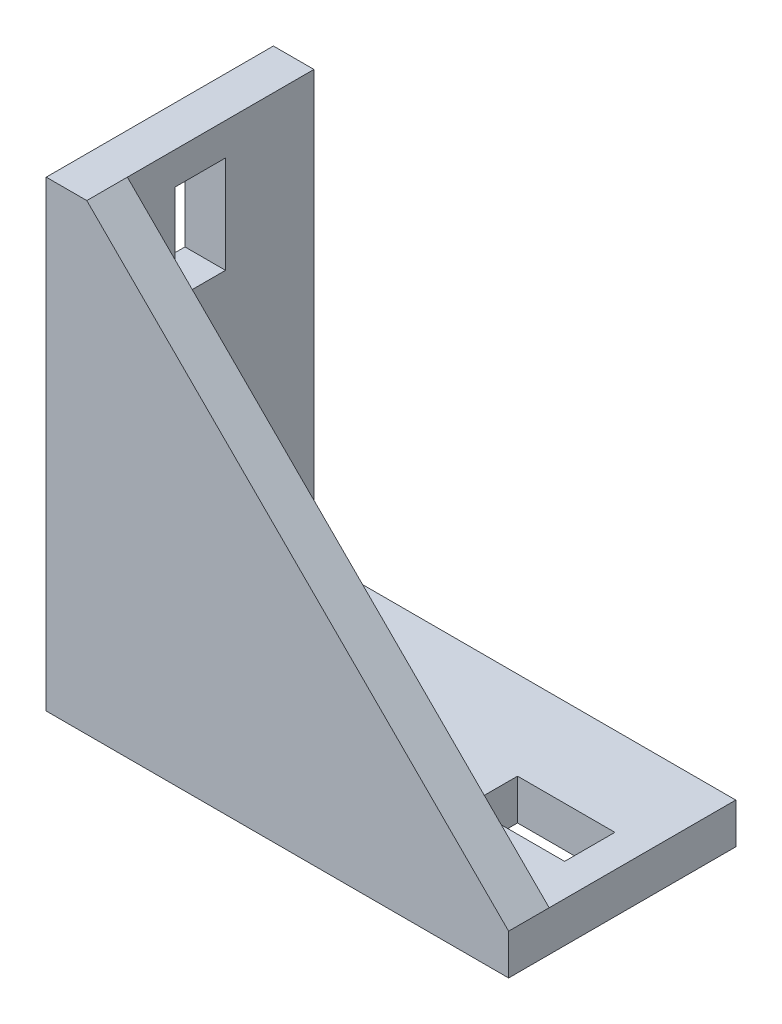
SolidWorks part; units mm, degrees
ref_plane "Front Plane" through (0, 0, 0) normal (0, 0, 1) x (1, 0, 0)
ref_plane "Top Plane" through (0, 0, 0) normal (0, 1, 0) x (1, 0, 0)
ref_plane "Right Plane" through (0, 0, 0) normal (1, 0, 0) x (0, 0, -1)
sketch "Sketch1" plane through (0, 0, 0) normal (0, 0, 1) x (1, 0, 0)
  line L0 (5, 57) -> (5, 5)
  line L1 (0, 0) -> (57, 0)
  line L2 (0, 0) -> (0, 57)
  line L3 (0, 57) -> (5, 57)
  line L4 (57, 5) -> (57, 0)
  line L5 (5, 5) -> (57, 5)
  dimension "D1" = 57
  dimension "D2" = 57
  dimension "D3" = 5
  dimension "D4" = 5
extrude "Boss-Extrude1" add sketch "Sketch1" along normal blind 28
sketch "Sketch2" plane through (0, 0, 28) normal (0, 0, 1) x (1, 0, 0)
  line L0 (5, 57) -> (57, 5)
  line L1 (5, 57) -> (5, 5)
  line L2 (5, 5) -> (57, 5)
extrude "Boss-Extrude2" add sketch "Sketch2" against normal blind 5
sketch "Sketch3" plane through (5, 0, 0) normal (1, 0, 0) x (0, 0, -1)
  line L0 (-28, 57) -> (0, 57) construction
  line L1 (-28, 57) -> (-23, 57) construction
  line L2 (-14, 57) -> (-14, 5) construction
  line L3 (-23, 5) -> (0, 5) construction
  line L7 (-17.1, 41) -> (-10.9, 41)
  line L8 (-17.1, 41) -> (-17.1, 53)
  line L9 (-17.1, 53) -> (-10.9, 53)
  line L10 (-10.9, 41) -> (-10.9, 53)
  line L11 (-17.1, 41) -> (-10.9, 53) construction
  line L12 (-17.1, 53) -> (-10.9, 41) construction
  line L13 (-17.1, 9) -> (-10.9, 9)
  line L14 (-17.1, 9) -> (-17.1, 21)
  line L15 (-17.1, 21) -> (-10.9, 21)
  line L16 (-10.9, 9) -> (-10.9, 21)
  line L17 (-17.1, 9) -> (-10.9, 21) construction
  line L18 (-17.1, 21) -> (-10.9, 9) construction
  point P9 (-14, 47)
  point P14 (-14, 15)
  point P21 (0, 0)
  dimension "D1" = 6.2
  dimension "D2" = 6.2
  dimension "D3" = 12
  dimension "D4" = 10
  dimension "D5" = 12
  dimension "D6" = 10
extrude "Cut-Extrude1" cut sketch "Sketch3" against normal blind 5
sketch "Sketch4" plane through (0, 5, 0) normal (0, 1, 0) x (1, 0, 0)
  line L0 (57, -28) -> (57, 0) construction
  line L1 (57, -14) -> (5, -14) construction
  line L2 (5, -23) -> (5, 0) construction
  line L4 (53, -17.1) -> (41, -17.1)
  line L5 (53, -17.1) -> (53, -10.9)
  line L6 (53, -10.9) -> (41, -10.9)
  line L7 (41, -17.1) -> (41, -10.9)
  line L8 (53, -17.1) -> (41, -10.9) construction
  line L9 (53, -10.9) -> (41, -17.1) construction
  line L10 (21, -17.1) -> (9, -17.1)
  line L11 (21, -17.1) -> (21, -10.9)
  line L12 (21, -10.9) -> (9, -10.9)
  line L13 (9, -17.1) -> (9, -10.9)
  line L14 (21, -17.1) -> (9, -10.9) construction
  line L15 (21, -10.9) -> (9, -17.1) construction
  point P8 (47, -14)
  point P13 (15, -14)
  dimension "D1" = 10
  dimension "D2" = 12
  dimension "D3" = 6.2
  dimension "D4" = 6.2
  dimension "D5" = 12
  dimension "D6" = 10
extrude "Cut-Extrude2" cut sketch "Sketch4" against normal blind 5
